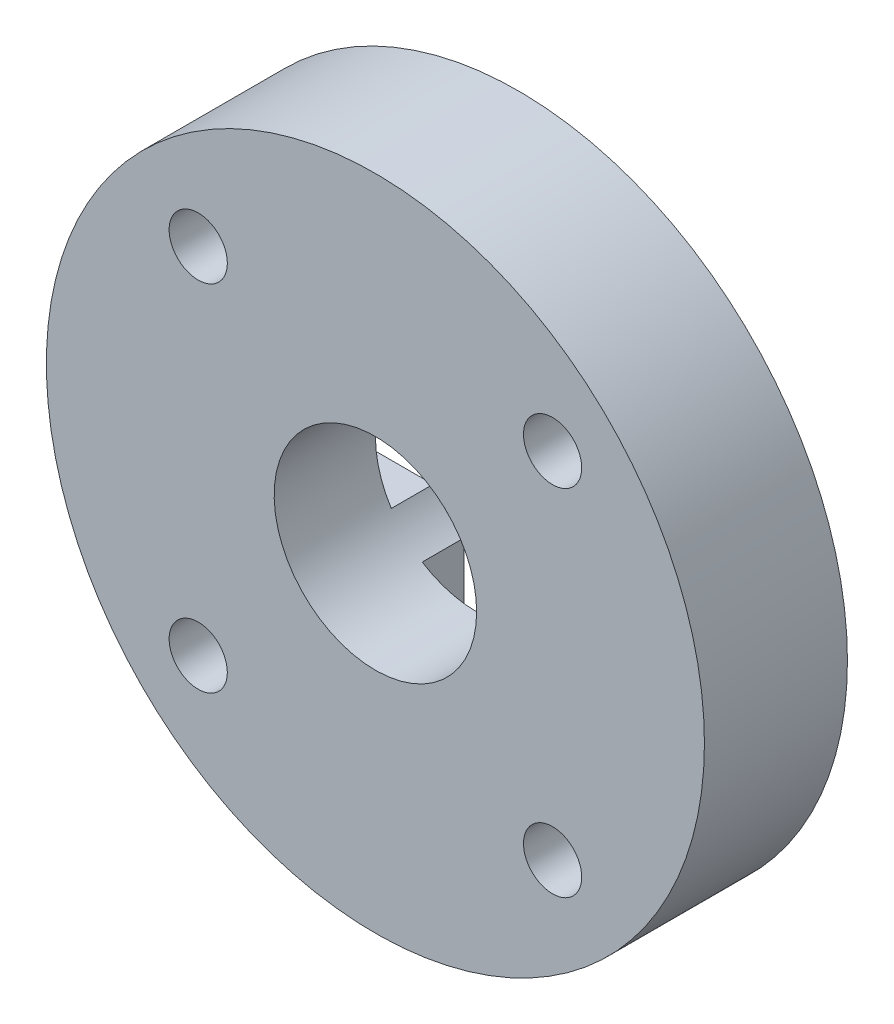
SolidWorks part; units mm, degrees
ref_plane "Front Plane" through (0, 0, 0) normal (0, 0, 1) x (1, 0, 0)
ref_plane "Top Plane" through (0, 0, 0) normal (0, 1, 0) x (1, 0, 0)
ref_plane "Right Plane" through (0, 0, 0) normal (1, 0, 0) x (0, 0, -1)
sketch "Trial_load_plate_profile" plane through (0, 0, 0) normal (0, 0, 1) x (1, 0, 0)
  circle A0 centre (0, 0) radius 13
  circle A1 centre (0, 0) radius 4
  dimension "D1" = 26
  dimension "D2" = 8
extrude "Trial_load_plate" add sketch "Trial_load_plate_profile" along normal blind 4
sketch "Captured_horn_key_boss_profile" plane through (0, 0, 0) normal (0, 0, 1) x (1, 0, 0)
  circle A0 centre (0, 0) radius 13
  dimension "D1" = 26
extrude "Captured_horn_key_boss" add sketch "Captured_horn_key_boss_profile" along normal blind 1.65 from offset 1.65
sketch "Stock_horn_pocket_Hub" plane through (0, 0, 0) normal (0, 0, 1) x (1, 0, 0)
  circle A0 centre (0, 0) radius 3.6
  dimension "D1" = 7.2
extrude "Key_pocket_Hub" cut sketch "Stock_horn_pocket_Hub" along normal blind 1.65 from offset 1.65
sketch "Stock_horn_pocket_Horizontal" plane through (0, 0, 0) normal (0, 0, 1) x (1, 0, 0)
  line L1 (-8.15, -2.15) -> (8.15, -2.15)
  line L2 (-8.15, -2.15) -> (-8.15, 2.15)
  line L3 (-8.15, 2.15) -> (8.15, 2.15)
  line L4 (8.15, -2.15) -> (8.15, 2.15)
  dimension "D1" = 16.3
  dimension "D2" = 4.3
  dimension "D3" = 8.15
  dimension "D4" = 2.15
extrude "Key_pocket_Horizontal" cut sketch "Stock_horn_pocket_Horizontal" along normal blind 1.65 from offset 1.65
sketch "Stock_horn_pocket_Vertical" plane through (0, 0, 0) normal (0, 0, 1) x (1, 0, 0)
  line L1 (-2.15, -8.15) -> (2.15, -8.15)
  line L2 (-2.15, -8.15) -> (-2.15, 8.15)
  line L3 (-2.15, 8.15) -> (2.15, 8.15)
  line L4 (2.15, -8.15) -> (2.15, 8.15)
  dimension "D1" = 4.3
  dimension "D2" = 16.3
  dimension "D3" = 2.15
  dimension "D4" = 8.15
extrude "Key_pocket_Vertical" cut sketch "Stock_horn_pocket_Vertical" along normal blind 1.65 from offset 1.65
sketch "Stock_horn_pocket_Rounded_tips" plane through (0, 0, 0) normal (0, 0, 1) x (1, 0, 0)
  circle A0 centre (8.15, 0) radius 2.15
  circle A1 centre (-8.15, 0) radius 2.15
  circle A2 centre (0, 8.15) radius 2.15
  circle A3 centre (0, -8.15) radius 2.15
  dimension "D1" = 4.3
  dimension "D2" = 4.3
  dimension "D3" = 4.3
  dimension "D4" = 4.3
  dimension "D5" = 8.15
  dimension "D6" = 8.15
  dimension "D7" = 8.15
  dimension "D8" = 8.15
extrude "Key_pocket_Rounded_tips" cut sketch "Stock_horn_pocket_Rounded_tips" along normal blind 1.65 from offset 1.65
sketch "Unmodified_horn_capture_M2_profile" plane through (0, 0, 0) normal (0, 0, 1) x (1, 0, 0)
  circle A0 centre (7, 7) radius 1.15
  circle A1 centre (-7, 7) radius 1.15
  circle A2 centre (-7, -7) radius 1.15
  circle A3 centre (7, -7) radius 1.15
  dimension "D1" = 2.3
  dimension "D2" = 2.3
  dimension "D3" = 2.3
  dimension "D4" = 2.3
  dimension "D5" = 7
  dimension "D6" = 7
  dimension "D7" = 7
  dimension "D8" = 7
extrude "Unmodified_horn_capture_M2" cut sketch "Unmodified_horn_capture_M2_profile" along normal through all from offset 50
sketch "Horn_center_hub_clearance" plane through (0, 0, 0) normal (0, 0, 1) x (1, 0, 0)
  circle A0 centre (0, 0) radius 4
  dimension "D1" = 8
extrude "Hub_clearance_in_key_boss_only" cut sketch "Horn_center_hub_clearance" along normal blind 1.65 from offset 1.65
